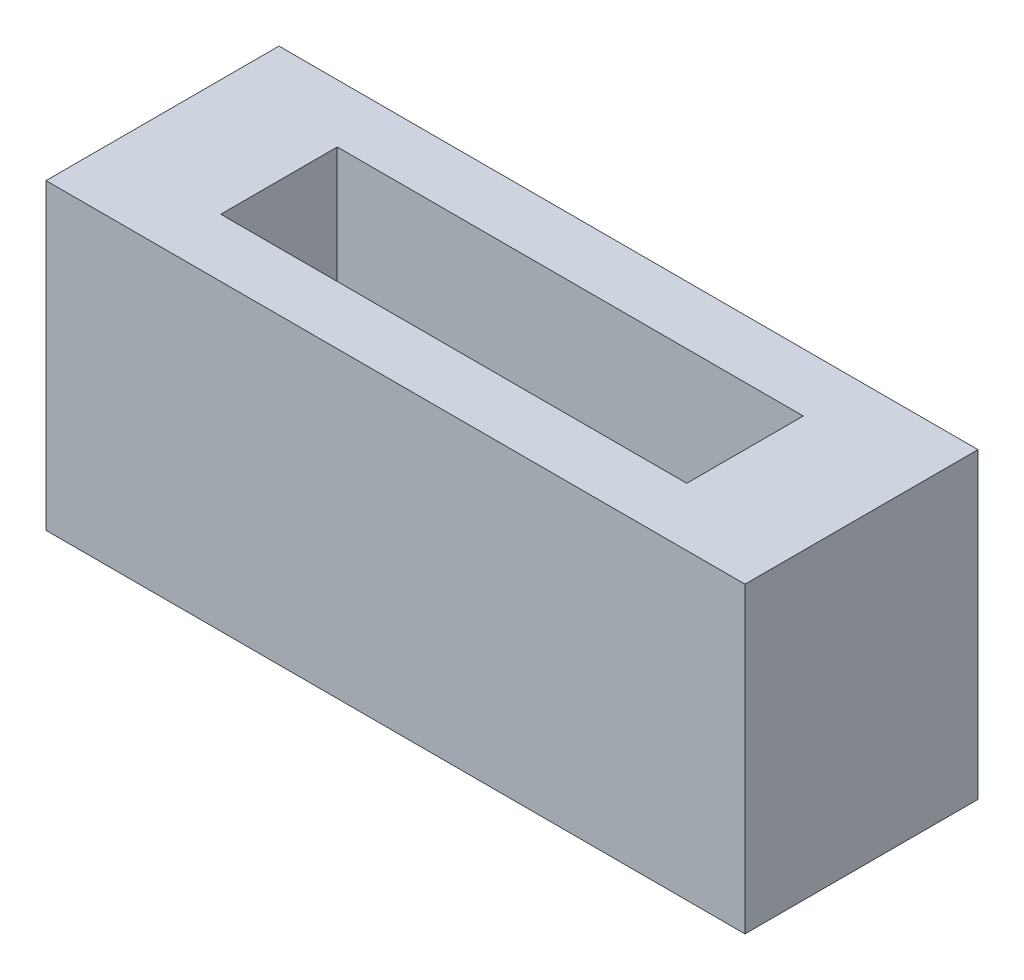
SolidWorks part; units mm, degrees
ref_plane "Front Plane" through (0, 0, 0) normal (0, 0, 1) x (1, 0, 0)
ref_plane "Top Plane" through (0, 0, 0) normal (0, 1, 0) x (1, 0, 0)
ref_plane "Right Plane" through (0, 0, 0) normal (1, 0, 0) x (0, 0, -1)
sketch "Sketch1" plane through (0, 0, 0) normal (0, 1, 0) x (1, 0, 0)
  line L1 (-19.05, -6.35) -> (19.05, -6.35)
  line L2 (-19.05, -6.35) -> (-19.05, 6.35)
  line L3 (-19.05, 6.35) -> (19.05, 6.35)
  line L4 (19.05, -6.35) -> (19.05, 6.35)
  line L5 (-19.05, -6.35) -> (19.05, 6.35) construction
  line L6 (-19.05, 6.35) -> (19.05, -6.35) construction
  point P0 (0, 0)
  dimension "D1" = 12.7
  dimension "D2" = 38.1
extrude "Boss-Extrude1" add sketch "Sketch1" along normal blind 16.51
sketch "Sketch2" plane through (0, 16.51, 0) normal (0, 1, 0) x (1, 0, 0)
  line L1 (-12.7, -3.175) -> (12.7, -3.175)
  line L2 (-12.7, -3.175) -> (-12.7, 3.175)
  line L3 (-12.7, 3.175) -> (12.7, 3.175)
  line L4 (12.7, -3.175) -> (12.7, 3.175)
  line L5 (-12.7, -3.175) -> (12.7, 3.175) construction
  line L6 (-12.7, 3.175) -> (12.7, -3.175) construction
  point P0 (0, 0)
  dimension "D1" = 6.35
  dimension "D2" = 25.4
extrude "Cut-Extrude1" cut sketch "Sketch2" against normal blind 12.7
